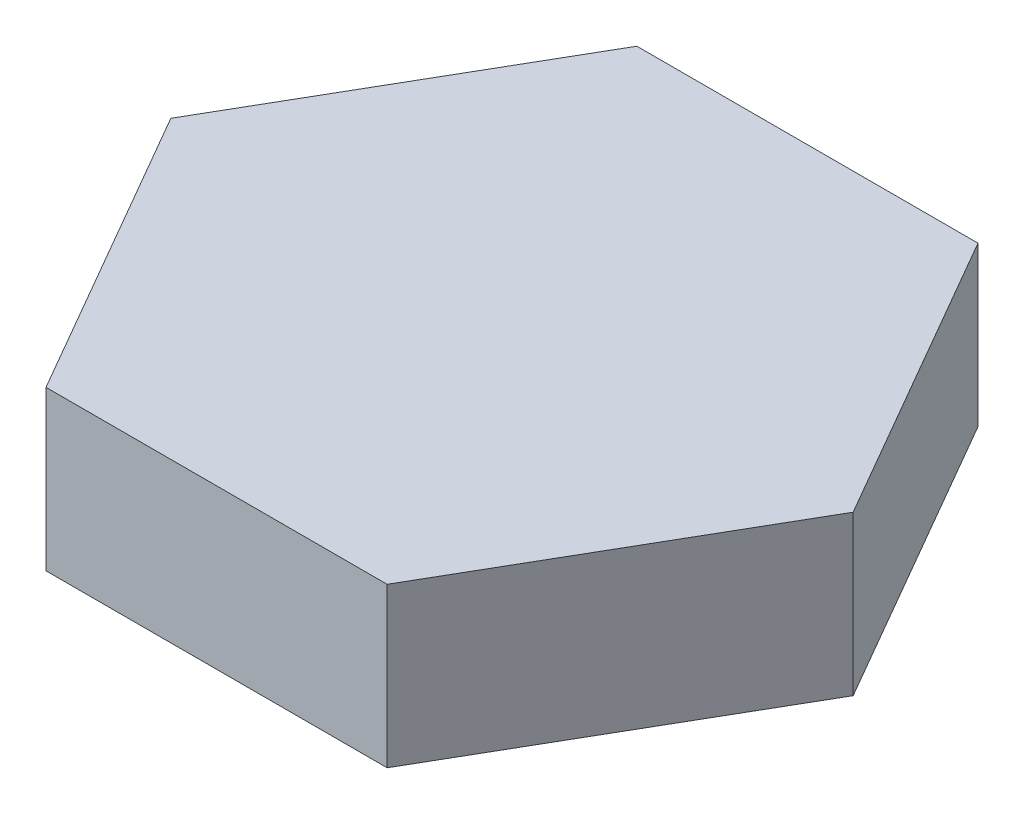
SolidWorks part; units mm, degrees
ref_plane "Front Plane" through (0, 0, 0) normal (0, 0, 1) x (1, 0, 0)
ref_plane "Top Plane" through (0, 0, 0) normal (0, 1, 0) x (1, 0, 0)
ref_plane "Right Plane" through (0, 0, 0) normal (1, 0, 0) x (0, 0, -1)
sketch "Sketch1" plane through (0, 0, 0) normal (0, 1, 0) x (1, 0, 0)
  line L0 (-48, 83.1384) -> (48, 83.1384)
  line L1 (48, 83.1384) -> (96, 0)
  line L2 (96, 0) -> (48, -83.1384)
  line L3 (48, -83.1384) -> (-48, -83.1384)
  line L4 (-48, -83.1384) -> (-96, 0)
  line L5 (-96, 0) -> (-48, 83.1384)
  line L6 (-48, -83.1384) -> (48, 83.1384) construction
  line L7 (48, -83.1384) -> (-48, 83.1384) construction
  line L8 (96, 0) -> (-96, 0) construction
  dimension "D1" = 120
  dimension "D2" = 96
extrude "Boss-Extrude1" add sketch "Sketch1" along normal up to surface (44.7242 mm away)
